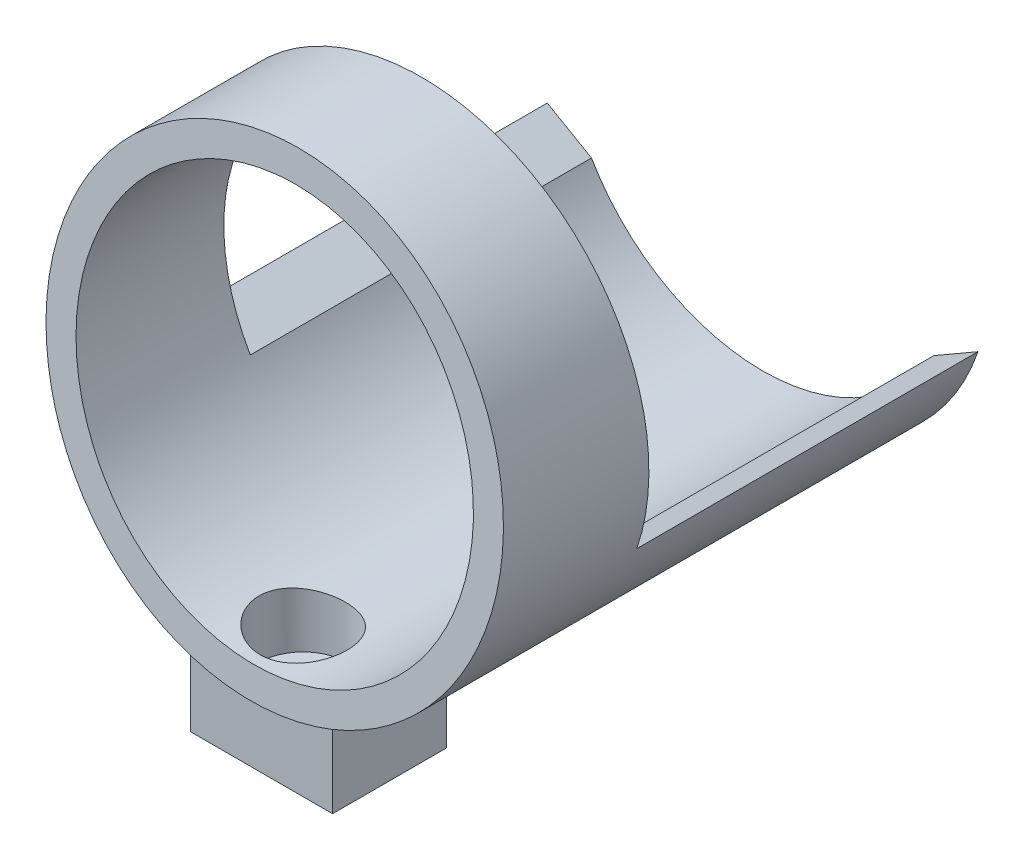
SolidWorks part; units mm, degrees
ref_plane "Front Plane" through (0, 0, 0) normal (0, 0, 1) x (1, 0, 0)
ref_plane "Top Plane" through (0, 0, 0) normal (0, 1, 0) x (1, 0, 0)
ref_plane "Right Plane" through (0, 0, 0) normal (1, 0, 0) x (0, 0, -1)
sketch "Sketch1" plane through (0, 0, 0) normal (0, 0, 1) x (1, 0, 0)
  circle A0 centre (0, 0) radius 16
  dimension "D1" = 32
extrude "Boss-Extrude1" add sketch "Sketch1" along normal blind 36
sketch "Sketch4" plane through (0, 0, 0) normal (0, 0, -1) x (-1, 0, 0)
  circle A0 centre (0, 0) radius 13.9
  dimension "D1" = 27.8
extrude "Cut-Extrude1" cut sketch "Sketch4" against normal through all
sketch "Sketch6" plane through (0, 0, 0) normal (1, 0, 0) x (0, 0, -1)
  line L0 (-36, 16) -> (-32.6367, 16)
  line L1 (0, 16) -> (-36, 16) construction
  line L2 (-32.6367, 16) -> (-36, -16)
  line L3 (-36, -16) -> (-36, 16)
  dimension "D1" = 6
extrude "Cut-Extrude3" cut sketch "Sketch6" against normal through all both and the other way through all
ref_plane "Plane1" through (0, -21, 0) normal (0, 1, 0) x (1, 0, 0)
sketch "Sketch8" plane through (0, -21, 0) normal (0, 1, 0) x (1, 0, 0)
  line L0 (0, 0) -> (0, -36) construction
  line L1 (4.75, -35) -> (-5.25, -35)
  line L2 (4.75, -35) -> (4.75, -27)
  line L3 (4.75, -27) -> (-5.25, -27)
  line L4 (-5.25, -35) -> (-5.25, -27)
  line L5 (4.75, -35) -> (-5.25, -27) construction
  line L6 (4.75, -27) -> (-5.25, -35) construction
  line L7 (-16.5752, -36) -> (16.5752, -36) construction
  ellipse E2 centre (0, -34.3183) end of major axis (-16, -34.3183) minor radius 1.6817 construction
  point P0 (-0.25, -31)
  point P17 (0, -36)
  dimension "D1" = 10
  dimension "D2" = 4.75
  dimension "D3" = 1
  dimension "D4" = 8
extrude "Boss-Extrude2" add sketch "Sketch8" along normal up to next
sketch "Sketch7" plane through (0, 0, 0) normal (0, 1, 0) x (1, 0, 0)
  line L0 (-0.45, 0) -> (-0.45, -35.9993) construction
  line L1 (14.5845, -24) -> (-22.6609, -24) construction
  line L2 (0, 0) -> (0, -24) construction
  circle A0 centre (-0.45, -31.8678) radius 1.7
  ellipse E0 centre (0, -34.3183) end of major axis (-16, -34.3183) minor radius 1.6817 construction
  point P5 (0, 0)
  dimension "D1" = 3.4
  dimension "D2" = 4.1315
  dimension "D3" = 0.45
extrude "Cut-Extrude4" cut sketch "Sketch7" against normal blind 25
sketch "Sketch10" plane through (0, 0, 0) normal (0, 1, 0) x (1, 0, 0)
  circle A0 centre (-0.45, -31.8678) radius 1.7 construction
  circle A1 centre (-0.45, -31.8678) radius 1.7 construction
  circle A2 centre (-0.45, -31.8678) radius 3.1
  dimension "D1" = 6.2
extrude "Cut-Extrude6" cut sketch "Sketch10" against normal blind 17.5 contours A2
sketch "Sketch11" plane through (0, 0, 0) normal (0, 0, -1) x (-1, 0, 0)
  line L0 (-51.7883, 16) -> (0, -13.9)
  line L1 (0, -13.9) -> (51.7883, 16)
  line L2 (51.7883, 16) -> (-51.7883, 16)
  line L3 (0, 16) -> (0, -13.9) construction
  circle A0 centre (0, 0) radius 13.9 construction
  arc A1 (-2.65, -13.6451) -> (3.55, -13.439) centre (0, 0) ccw construction
  circle A2 centre (0, 0) radius 16 construction
  point P5 (0, 0)
  point P6 (0, -12.5)
  dimension "D1" = 120
extrude "Cut-Extrude7" cut sketch "Sketch11" against normal blind 24
